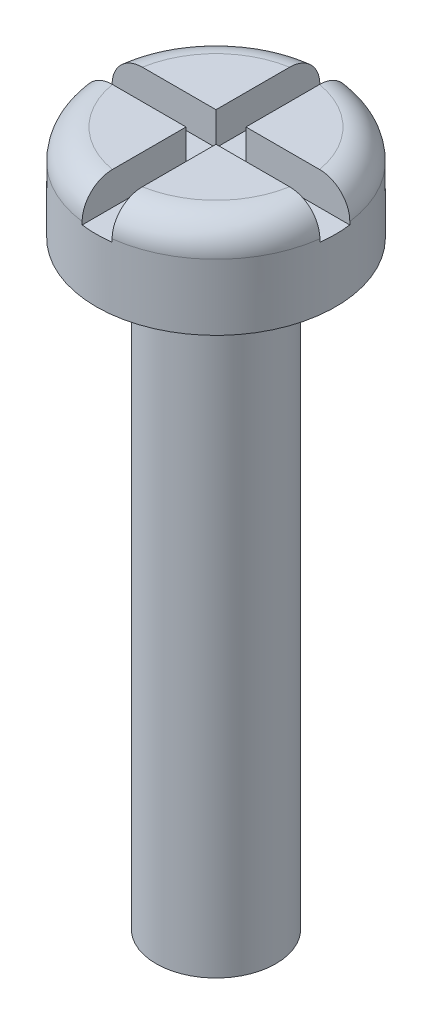
SolidWorks part; units mm, degrees
ref_plane "Front Plane" through (0, 0, 0) normal (0, 0, 1) x (1, 0, 0)
ref_plane "Top Plane" through (0, 0, 0) normal (0, 1, 0) x (1, 0, 0)
ref_plane "Right Plane" through (0, 0, 0) normal (1, 0, 0) x (0, 0, -1)
sketch "Sketch1" plane through (0, 0, 0) normal (0, 1, 0) x (1, 0, 0)
  circle A0 centre (0, 0) radius 2
  dimension "D1" = 4
extrude "Boss-Extrude1" add sketch "Sketch1" along normal blind 1.6
sketch "Sketch2" plane through (0, 0, 0) normal (0, -1, 0) x (1, 0, 0)
  circle A0 centre (0, 0) radius 1
extrude "Boss-Extrude2" add sketch "Sketch2" along normal blind 10
fillet "Fillet1" radius 0.5 1 edges at (0, 1.6, 2)
sketch "Sketch3" plane through (0, 1.6, 0) normal (0, 1, 0) x (1, 0, 0)
  line L0 (0, 0.25) -> (0, 0) construction
  line L2 (-2, -0.25) -> (-0.25, -0.25)
  line L3 (-0.25, 2) -> (-0.25, 0.25)
  line L4 (-2, 0.25) -> (-0.25, 0.25)
  line L5 (0.25, 2) -> (0.25, 0.25)
  line L6 (-0.25, 2) -> (-0.0677, 2.2984)
  line L7 (-0.0677, 2.2984) -> (0.25, 2)
  line L8 (2, 0.25) -> (2, -0.25)
  line L9 (0.25, -2) -> (-0.25, -2)
  line L10 (-2, 0.25) -> (-2, -0.25)
  line L11 (0, 2) -> (0, -2) construction
  line L12 (0.25, 0.25) -> (2, 0.25)
  line L17 (-0.25, -0.25) -> (-0.25, -2)
  line L18 (-0.25, 2) -> (-0.25, -2) construction
  line L19 (0.25, -0.25) -> (2, -0.25)
  line L21 (0.25, -0.25) -> (0.25, -2)
  line L22 (0.25, 2) -> (0.25, -2) construction
  dimension "D1" = 0.25
  dimension "D2" = 0.25
extrude "Cut-Extrude1" cut sketch "Sketch3" against normal blind 0.55
